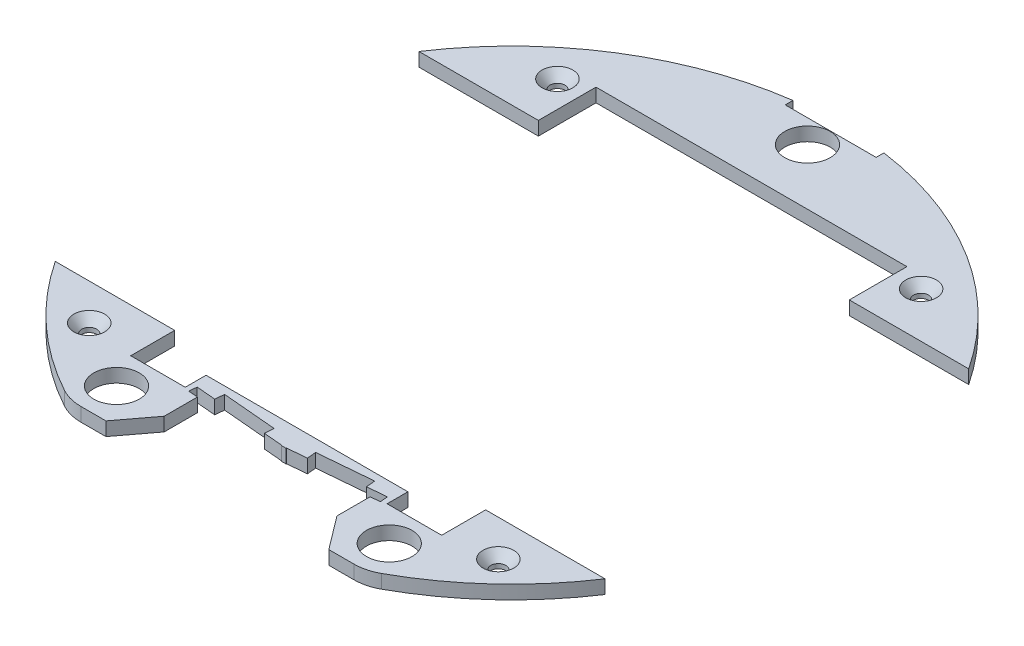
SolidWorks part; units mm, degrees
ref_plane "Front Plane" through (0, 0, 0) normal (0, 0, 1) x (1, 0, 0)
ref_plane "Top Plane" through (0, 0, 0) normal (0, 1, 0) x (1, 0, 0)
ref_plane "Right Plane" through (0, 0, 0) normal (1, 0, 0) x (0, 0, -1)
sketch "Sketch1" plane through (0, 0, 0) normal (0, 1, 0) x (1, 0, 0)
  line L0 (-30.03, -64.8129) -> (30.03, -64.8129)
  line L1 (0, -85) -> (0, 0) construction
  line L2 (0, -85) -> (32.4891, -64.8129) construction
  arc A0 (34.8348, -63.5829) -> (-34.8348, -63.5829) centre (0, 0) ccw
  circle A1 centre (0, -85) radius 38.25 construction
  arc A2 (30.03, -64.8129) -> (34.8348, -63.5829) centre (30.03, -54.8129) ccw
  arc A3 (-30.03, -64.8129) -> (-34.8348, -63.5829) centre (-30.03, -54.8129) cw
  dimension "D1" = 145
  dimension "D2" = 76.5
  dimension "D4" = 10
  dimension "D3" = 85
extrude "Boss-Extrude1" add sketch "Sketch1" along normal blind 3
sketch "Sketch2" plane through (0, 3, 0) normal (0, 1, 0) x (1, 0, 0)
  line L5 (22.2, -49.6757) -> (22.2, -45.1)
  line L6 (22.2, -45.1) -> (-22.2, -45.1)
  line L7 (-22.2, -45.1) -> (-22.2, -49.6757)
  line L8 (22.2, 49.6757) -> (22.2, 45.5)
  line L9 (-34.2, -49.6757) -> (-22.2, -49.6757) construction
  line L10 (-34.2, -49.6757) -> (-34.2, 49.6757) construction
  line L11 (-34.2, 49.6757) -> (-22.2, 49.6757) construction
  line L19 (34.2, 49.6757) -> (22.2, 49.6757) construction
  line L20 (34.2, -49.6757) -> (34.2, 49.6757) construction
  line L21 (34.2, -49.6757) -> (22.2, -49.6757) construction
  line L22 (22.2, 45.5) -> (-22.2, 45.5)
  line L23 (-22.2, 45.5) -> (-22.2, 49.6757)
  line L35 (-34.2, -49.6757) -> (-22.2, -49.6757)
  line L36 (-34.2, -49.6757) -> (-34.2, 49.6757)
  line L37 (-34.2, 49.6757) -> (-22.2, 49.6757)
  line L55 (34.2, 49.6757) -> (22.2, 49.6757)
  line L56 (34.2, -49.6757) -> (34.2, 49.6757)
  line L57 (34.2, -49.6757) -> (22.2, -49.6757)
  dimension "D1" = 45.1
  dimension "D2" = 45.5
extrude "Cut-Extrude1" cut sketch "Sketch2" against normal through all
sketch "Sketch3" plane through (0, 3, 0) normal (0, 1, 0) x (1, 0, 0)
  line L0 (-34.2, 40) -> (-34.2, -40)
  line L1 (-72.5, -40) -> (-34.2, -40)
  line L2 (-72.5, -40) -> (-72.5, 40)
  line L3 (-72.5, 40) -> (-34.2, 40)
  line L4 (72.5, -40) -> (72.5, 40)
  line L5 (-72.5, -40) -> (72.5, 40) construction
  line L6 (-72.5, 40) -> (72.5, -40) construction
  line L7 (-34.2, -49.6757) -> (-34.2, 49.6757) construction
  line L8 (34.2, 40) -> (34.2, -40)
  line L9 (34.2, -49.6757) -> (34.2, 49.6757) construction
  line L10 (34.2, 40) -> (72.5, 40)
  line L11 (34.2, -40) -> (72.5, -40)
  arc A0 (34.8348, -63.5829) -> (-34.8348, -63.5829) centre (0, 0) ccw construction
  point P0 (0, 0)
  dimension "D1" = 80
extrude "Cut-Extrude2" cut sketch "Sketch3" against normal through all
sketch "Sketch4" plane through (0, 3, 0) normal (0, 1, 0) x (1, 0, 0)
  line L0 (-21.0702, -50.0262) -> (-0.6482, -51.8129)
  line L1 (21.0702, -50.0262) -> (20.922, -48.3326)
  line L2 (0.6482, -51.8129) -> (0.5, -50.1193)
  line L3 (20.922, -48.3326) -> (0.5, -50.1193)
  line L4 (0, 0) -> (0, -64.8129) construction
  line L5 (-30.03, -64.8129) -> (30.03, -64.8129) construction
  line L6 (-20.922, -48.3326) -> (-0.5, -50.1193)
  line L7 (-0.6482, -51.8129) -> (-0.5, -50.1193)
  line L8 (-21.0702, -50.0262) -> (-20.922, -48.3326)
  line L14 (21.0702, -50.0262) -> (0.6482, -51.8129)
  dimension "D1" = 1.7
  dimension "D2" = 20.5
  dimension "D3" = 5
  dimension "D4" = 13
  dimension "D5" = 0.5
extrude "Cut-Extrude3" cut sketch "Sketch4" against normal through all
sketch "Sketch5" plane through (0, 3, 0) normal (0, 1, 0) x (1, 0, 0)
  line L0 (-19, -64.8129) -> (-19, -50.2073)
  line L4 (0.6482, -51.8129) -> (21.0702, -50.0262) construction
  line L5 (16.6882, -48.7031) -> (4.7338, -49.7489)
  line L6 (16.6882, -48.7031) -> (16.5139, -46.7107)
  line L7 (4.7338, -49.7489) -> (4.5595, -47.7565)
  line L8 (16.5139, -46.7107) -> (4.5595, -47.7565)
  line L9 (20.922, -48.3326) -> (0.5, -50.1193) construction
  line L10 (0, 0) -> (0, -50.2073) construction
  line L11 (19, -64.8129) -> (19, -50.2073)
  line L13 (-16.5139, -46.7107) -> (-4.5595, -47.7565)
  line L14 (-4.7338, -49.7489) -> (-4.5595, -47.7565)
  line L15 (-16.6882, -48.7031) -> (-16.5139, -46.7107)
  line L16 (-16.6882, -48.7031) -> (-4.7338, -49.7489)
  line L22 (-30.03, -64.8129) -> (30.03, -64.8129) construction
  line L23 (19, -50.2073) -> (-19, -50.2073)
  line L25 (-19, -64.8129) -> (19, -64.8129)
  point P14 (10.711, -49.226)
  point P15 (10.711, -49.226)
  dimension "D1" = 12
  dimension "D2" = 38
  dimension "D4" = 2
extrude "Cut-Extrude4" cut sketch "Sketch5" against normal through all
sketch "Sketch6" plane through (0, 3, 0) normal (0, 1, 0) x (1, 0, 0)
  line L1 (34.2, 49.6757) -> (-34.2, 49.6757)
  line L2 (34.2, 49.6757) -> (34.2, 52.6757)
  line L3 (34.2, 52.6757) -> (-34.2, 52.6757)
  line L4 (-34.2, 49.6757) -> (-34.2, 52.6757)
  point P4 (-34.2, 49.6757)
  dimension "D1" = 3
extrude "Cut-Extrude5" cut sketch "Sketch6" against normal through all
sketch "Sketch7" plane through (0, 3, 0) normal (0, 1, 0) x (1, 0, 0)
  line L0 (0, 0) -> (0, -31.2827) construction
  circle A0 centre (-30, -57) radius 5
  circle A4 centre (30, -57) radius 5
  dimension "D1" = 10
  dimension "D2" = 30
  dimension "D3" = 57
extrude "Cut-Extrude6" cut sketch "Sketch7" against normal through all
sketch "Sketch11" plane through (0, 3, 0) normal (0, 1, 0) x (1, 0, 0)
  line L0 (0, 0) -> (0, 65) construction
  circle A0 centre (0, 65) radius 5
  dimension "D2" = 10
  dimension "D1" = 65
extrude "Cut-Extrude10" cut sketch "Sketch11" against normal through all
sketch "Sketch13" plane through (0, 3, 0) normal (0, 1, 0) x (1, 0, 0)
  line L0 (19, -57.5101) -> (24.515, -64.8129)
  line L1 (19, -64.8129) -> (19, -50.2073) construction
  line L2 (19, -64.8129) -> (30.03, -64.8129) construction
  line L3 (24.515, -64.8129) -> (19, -64.8129)
  line L4 (19, -64.8129) -> (19, -57.5101)
  line L5 (0, 0) -> (0, -25.0729) construction
  line L6 (-19, -64.8129) -> (-19, -57.5101)
  line L7 (-24.515, -64.8129) -> (-19, -64.8129)
  line L8 (-19, -57.5101) -> (-24.515, -64.8129)
extrude "Cut-Extrude11" cut sketch "Sketch13" against normal through all
sketch "Sketch14" plane through (0, 3, 0) normal (0, 1, 0) x (1, 0, 0)
  line L1 (0, 0) -> (0, -20.685) construction
  circle A0 centre (45, -48) radius 1.65
  circle A1 centre (-45, -48) radius 1.65
  circle A2 centre (40, 50) radius 1.65
  circle A3 centre (-40, 50) radius 1.65
  dimension "D3" = 3.3
  dimension "D1" = 45
  dimension "D2" = 48
  dimension "D4" = 40
  dimension "D5" = 50
extrude "Cut-Extrude12" cut sketch "Sketch14" against normal through all
sketch "Sketch15" plane through (0, 3, 0) normal (0, 1, 0) x (1, 0, 0)
  line L1 (10, 71.807) -> (-10, 71.807)
  line L2 (10, 71.807) -> (10, 70.107)
  line L3 (10, 70.107) -> (-10, 70.107)
  line L4 (-10, 71.807) -> (-10, 70.107)
  arc A0 (60.4669, 40) -> (-60.4669, 40) centre (0, 0) ccw construction
  point P7 (-16.3798, 70.6254)
  dimension "D1" = 20
  dimension "D2" = 1.7
extrude "Cut-Extrude13" cut sketch "Sketch15" against normal blind 10
chamfer "Chamfer1" distance 2 angle 41 2 edges at (-45, 3, 46.35) (45, 3, 49.65)
chamfer "Chamfer2" distance 2 angle 41 2 edges at (-40, 3, -51.65) (40, 3, -48.35)
equation "\"smallPulleyTeeth\"= 30"
equation "\"largePulleyTeeth\"= 30"
equation "\"eighthThick\"= 3.0mm"
equation "\"sixteenthThick\" = 1.7mm"
equation "\"quarterThick\"=6.0mm"
equation "\"OD\" = 145mm"
equation "\"puckAngle\" = 60.5deg"
equation "\"puckDiam\" = 76.5mm"
equation "\"axlePress\" = 5.9mm"
equation "\"press\" = 0.2mm"
equation "\"wheelClear\" = 0.3mm"
equation "\"10-32clear\" = 4.8mm"
equation "\"6-32clear\" = 3.3mm"
equation "\"8-32clear\" = 4.0mm"
equation "\"4-40clear\" = 3.0mm"
equation "\"wheelHeight\" = 22mm"
equation "\"wheelWell\" = 65mm"
equation "\"D1@Sketch1\"=\"OD\""
equation "\"D1@Boss-Extrude1\"=\"eighthThick\""
equation "\"D2@Sketch1\"=\"puckDiam\""
equation "\"puckDist\" = 85mm"
equation "\"scoopFillet\" = 5mm"
equation "\"10-32tap\" = 4.45mm"
equation "\"ledSmall\" = 3.1mm"
equation "\"ledLarge\" = 4.2mm"
equation "\"ledLength\" = 4.2mm"
equation "\"D3@Sketch1\"=\"puckDist\""
equation "\"D1@Sketch6\"=\"eighthThick\""
equation "\"D2@Sketch15\"=\"sixteenthThick\""
